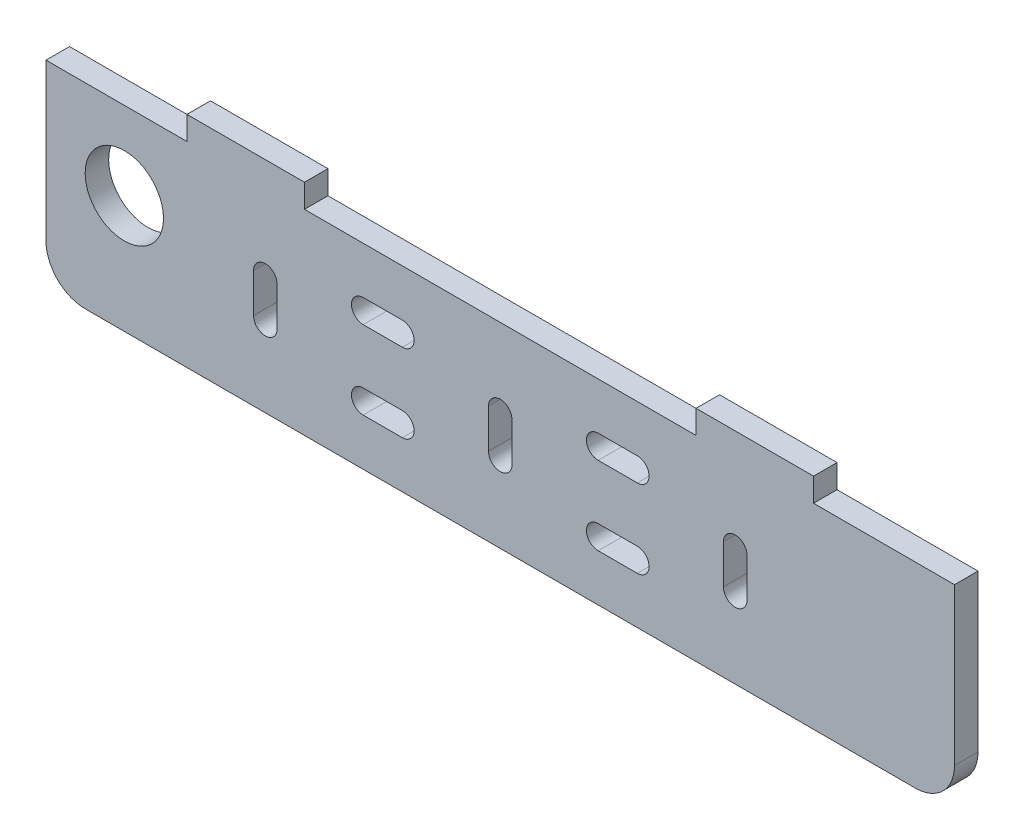
SolidWorks part; units mm, degrees
material "ABS"
ref_plane "Front Plane" through (0, 0, 0) normal (0, 0, 1) x (1, 0, 0)
ref_plane "Top Plane" through (0, 0, 0) normal (0, 1, 0) x (1, 0, 0)
ref_plane "Right Plane" through (0, 0, 0) normal (1, 0, 0) x (0, 0, -1)
sketch "Sketch1" plane through (0, 0, 0) normal (0, 0, 1) x (1, 0, 0)
  line L0 (-25, 0) -> (25, 0)
  line L1 (-58, 0) -> (-40, 0)
  line L2 (-58, 0) -> (-58, -20)
  line L3 (-53, -25) -> (53, -25)
  line L4 (58, 0) -> (58, -20)
  line L5 (40, 0) -> (58, 0)
  line L6 (-40, 0) -> (-40, 3)
  line L7 (-40, 3) -> (-25, 3)
  line L8 (-25, 0) -> (-25, 3)
  line L10 (25, 0) -> (25, 3)
  line L11 (25, 3) -> (40, 3)
  line L12 (40, 0) -> (40, 3)
  arc A0 (53, -25) -> (58, -20) centre (53, -20) ccw
  arc A1 (-53, -25) -> (-58, -20) centre (-53, -20) cw
  point P16 (58, -25)
  point P19 (-58, -25)
  dimension "D6" = 5
  dimension "D1" = 25
  dimension "D2" = 116
  dimension "D3" = 3
  dimension "D4" = 15
  dimension "D5" = 50
extrude "Boss-Extrude1" add sketch "Sketch1" along normal blind 3
sketch "Sketch2" plane through (0, 0, 3) normal (0, 0, 1) x (1, 0, 0)
  line L0 (-1.5, 0) -> (-1.5, -7)
  line L1 (25, 0) -> (-25, 0) construction
  line L2 (-1.5, -7) -> (-2.75, -7)
  line L3 (-2.75, -7) -> (-2.75, -10)
  line L4 (-2.75, -10) -> (-1.5, -10)
  line L5 (-1.5, -10) -> (-1.5, -14)
  line L6 (-1.5, -14) -> (1.5, -14)
  line L7 (1.5, -14) -> (1.5, -10)
  line L8 (1.5, -10) -> (2.75, -10)
  line L9 (2.75, -10) -> (2.75, -7)
  line L10 (2.75, -7) -> (1.5, -7)
  line L11 (1.5, -7) -> (1.5, 0)
  line L12 (1.5, 0) -> (-1.5, 0)
  dimension "D1" = 3
  dimension "D2" = 3
  dimension "D3" = 5.5
  dimension "D4" = 7
  dimension "D5" = 14
extrude "Cut-Extrude1" [suppressed] cut sketch "Sketch2" against normal through all
sketch "Sketch3" plane through (0, 0, 0) normal (0, 0, -1) x (-1, 0, 0)
  line L0 (48, -10) -> (58, -10) construction
  line L1 (58, 0) -> (58, -20) construction
  line L2 (48, -10) -> (48, -25) construction
  line L3 (53, -25) -> (-53, -25) construction
  circle A0 centre (48, -10) radius 5
  dimension "D1" = 10
  dimension "D2" = 15
  dimension "D3" = 10
extrude "Cut-Extrude2" cut sketch "Sketch3" against normal through all
sketch "Sketch4" plane through (0, 0, 0) normal (0, 0, -1) x (-1, 0, 0)
  line L0 (-30, -10) -> (-30, -15) construction
  line L1 (-28.5, -10) -> (-28.5, -15)
  line L2 (-31.5, -10) -> (-31.5, -15)
  line L3 (-17.5, -7.5) -> (-12.5, -7.5) construction
  line L4 (-17.5, -6) -> (-12.5, -6)
  line L5 (-17.5, -9) -> (-12.5, -9)
  line L6 (0, -15) -> (0, -10) construction
  line L7 (-1.5, -15) -> (-1.5, -10)
  line L8 (1.5, -15) -> (1.5, -10)
  line L9 (30, -15) -> (30, -10) construction
  line L10 (28.5, -15) -> (28.5, -10)
  line L11 (31.5, -15) -> (31.5, -10)
  line L12 (12.5, -7.5) -> (17.5, -7.5) construction
  line L13 (12.5, -6) -> (17.5, -6)
  line L14 (12.5, -9) -> (17.5, -9)
  line L15 (12.5, -17.5) -> (17.5, -17.5) construction
  line L16 (12.5, -16) -> (17.5, -16)
  line L17 (12.5, -19) -> (17.5, -19)
  line L18 (-17.5, -17.5) -> (-12.5, -17.5) construction
  line L19 (-17.5, -16) -> (-12.5, -16)
  line L20 (-17.5, -19) -> (-12.5, -19)
  line L21 (-15, -7.5) -> (-15, -17.5) construction
  line L22 (-30, -12.5) -> (-15, -12.5) construction
  line L23 (-15, -12.5) -> (0, -12.5) construction
  line L24 (0, -12.5) -> (15, -12.5) construction
  line L25 (15, -12.5) -> (30, -12.5) construction
  line L26 (15, -7.5) -> (15, -12.5) construction
  line L27 (15, -12.5) -> (15, -17.5) construction
  line L28 (53, -25) -> (-53, -25) construction
  line L29 (0, 0) -> (0, -12.5) construction
  arc A0 (-28.5, -10) -> (-31.5, -10) centre (-30, -10) ccw
  arc A1 (-31.5, -15) -> (-28.5, -15) centre (-30, -15) ccw
  arc A2 (-17.5, -6) -> (-17.5, -9) centre (-17.5, -7.5) ccw
  arc A3 (-12.5, -9) -> (-12.5, -6) centre (-12.5, -7.5) ccw
  arc A4 (-1.5, -15) -> (1.5, -15) centre (0, -15) ccw
  arc A5 (1.5, -10) -> (-1.5, -10) centre (0, -10) ccw
  arc A6 (28.5, -15) -> (31.5, -15) centre (30, -15) ccw
  arc A7 (31.5, -10) -> (28.5, -10) centre (30, -10) ccw
  arc A8 (12.5, -6) -> (12.5, -9) centre (12.5, -7.5) ccw
  arc A9 (17.5, -9) -> (17.5, -6) centre (17.5, -7.5) ccw
  arc A10 (12.5, -16) -> (12.5, -19) centre (12.5, -17.5) ccw
  arc A11 (17.5, -19) -> (17.5, -16) centre (17.5, -17.5) ccw
  arc A12 (-17.5, -16) -> (-17.5, -19) centre (-17.5, -17.5) ccw
  arc A13 (-12.5, -19) -> (-12.5, -16) centre (-12.5, -17.5) ccw
  point P2 (-30, -12.5)
  point P7 (-15, -7.5)
  point P14 (0, -12.5)
  point P21 (30, -12.5)
  point P28 (15, -7.5)
  point P35 (15, -17.5)
  point P42 (-15, -17.5)
  dimension "D2" = 1.5
  dimension "D1" = 5
  dimension "D3" = 12.5
  dimension "D4" = 10
  dimension "D5" = 15
extrude "Cut-Extrude3" cut sketch "Sketch4" against normal through all
